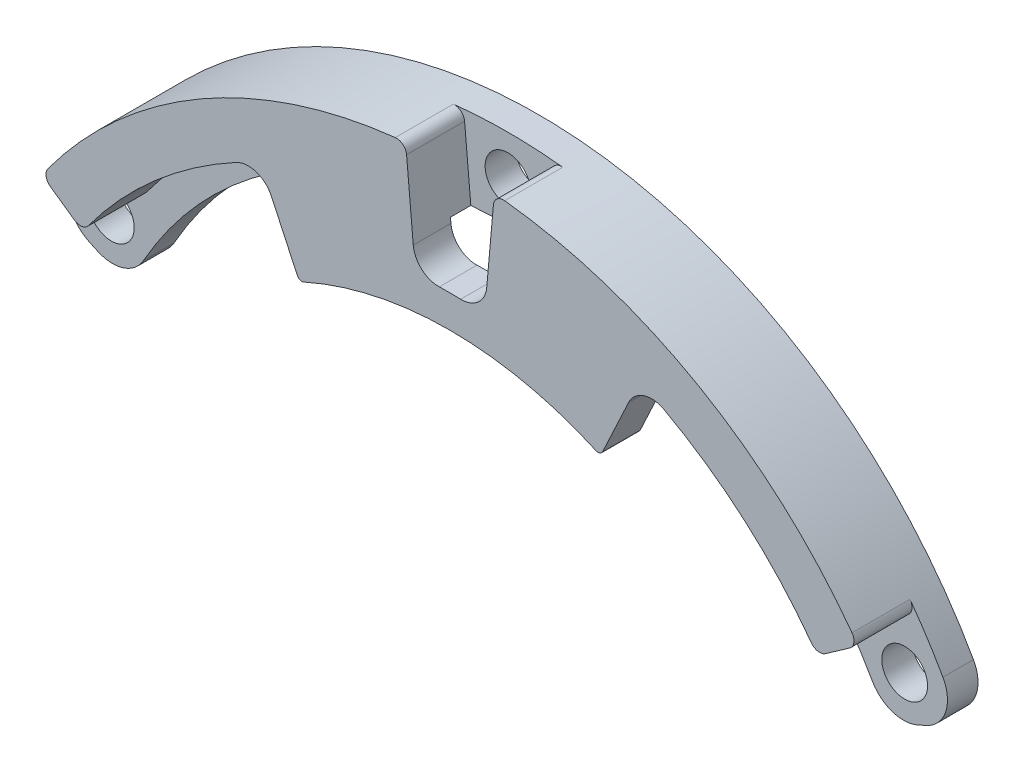
SolidWorks part; units mm, degrees
ref_plane "前视基准面" through (0, 0, 0) normal (0, 0, 1) x (1, 0, 0)
ref_plane "上视基准面" through (0, 0, 0) normal (0, 1, 0) x (1, 0, 0)
ref_plane "右视基准面" through (0, 0, 0) normal (1, 0, 0) x (0, 0, -1)
ref_plane "基准面1" through (0, 0, 8.7) normal (0, 0, 1) x (1, 0, 0)
sketch "草图1" plane through (0, 0, 8.7) normal (0, 0, 1) x (1, 0, 0)
  line L0 (14.7916, 31.7208) -> (18.6375, 39.9682)
  line L1 (36.0805, 25.3575) -> (40.0895, 28.175)
  line L2 (4.3556, 48.806) -> (3.3935, 38.0258)
  line L3 (-3.3935, 38.0258) -> (-4.3556, 48.806)
  line L4 (-40.0895, 28.175) -> (-36.0805, 25.3575)
  line L5 (-18.6375, 39.9682) -> (-14.7916, 31.7208)
  arc A0 (18.6375, 39.9682) -> (36.0805, 25.3575) centre (0, 0) cw
  arc A1 (40.0895, 28.175) -> (4.3556, 48.806) centre (0, 0) ccw
  arc A2 (3.3935, 38.0258) -> (-3.3935, 38.0258) centre (0, 0) ccw
  arc A3 (-4.3556, 48.806) -> (-40.0895, 28.175) centre (0, 0) ccw
  arc A4 (-36.0805, 25.3575) -> (-18.6375, 39.9682) centre (0, 0) cw
  arc A5 (-14.7916, 31.7208) -> (14.7916, 31.7208) centre (0, 0) cw
extrude "凸台-拉伸1" add sketch "草图1" against normal blind 3.7
sketch "草图2" plane through (0, 0, 5) normal (0, 0, -1) x (-1, 0, 0)
  line L0 (-36.0805, 25.3575) -> (-40.0895, 28.175)
  line L1 (-4.3556, 48.806) -> (-3.6533, 40.9373)
  line L2 (-17.3696, 37.2493) -> (-18.6375, 39.9682)
  arc A0 (-40.0895, 28.175) -> (-4.3556, 48.806) centre (0, 0) cw
  arc A1 (-3.6533, 40.9373) -> (-17.3696, 37.2493) centre (0, 0) ccw
  arc A2 (-18.6375, 39.9682) -> (-36.0805, 25.3575) centre (0, 0) ccw
extrude "凸台-拉伸2" add sketch "草图2" along normal blind 2
sketch "草图3" plane through (0, 0, 5) normal (0, 0, -1) x (-1, 0, 0)
  line L0 (3.6533, 40.9373) -> (4.3556, 48.806)
  line L1 (40.0895, 28.175) -> (36.0805, 25.3575)
  line L2 (18.6375, 39.9682) -> (17.3696, 37.2493)
  arc A0 (4.3556, 48.806) -> (40.0895, 28.175) centre (0, 0) cw
  arc A1 (36.0805, 25.3575) -> (18.6375, 39.9682) centre (0, 0) ccw
  arc A2 (17.3696, 37.2493) -> (3.6533, 40.9373) centre (0, 0) ccw
extrude "凸台-拉伸3" add sketch "草图3" along normal blind 2
ref_plane "基准面2" through (0, 0, 3) normal (0, 0, 1) x (1, 0, 0)
sketch "草图4" plane through (0, 0, 3) normal (0, 0, 1) x (1, 0, 0)
  line L0 (-44.445, 20.631) -> (-37.2794, 17.3048)
  line L1 (37.2794, 17.3048) -> (44.445, 20.631)
  arc A0 (-37.2794, 17.3048) -> (37.2794, 17.3048) centre (0, 0) cw
  arc A1 (44.445, 20.631) -> (-44.445, 20.631) centre (0, 0) ccw
extrude "凸台-拉伸4" add sketch "草图4" against normal blind 3
hole_wizard "Ø4.5 (4.5) 直径孔1" positions "草图6" profile "草图5" hole size "Ø4.5" standard "ANSI Metric"
sketch "草图6" plane through (0, 0, 3) normal (0, 0, 1) x (1, 0, 0)
  point P0 (-38.9711, 22.5)
  point P1 (38.9711, 22.5)
  point P2 (0, 45)
sketch "草图5" plane through (-38.9711, 22.5, 3) normal (1, 0, 0) x (0, -1, 0)
  line L0 (0, 0) -> (0, 3)
  line L1 (0, 3) -> (2.25, 3)
  line L2 (2.25, 3) -> (2.25, 0)
  line L5 (2.25, 0) -> (0, 0)
  line L11 (0, -6.35) -> (0, 107.95) construction
  dimension "通孔孔直径" = 4.5
  dimension "通孔孔深度" = 3
fillet "圆角1" radius 0.5 2 edges at (-14.7916, 31.7208, 6.85) (14.7916, 31.7208, 6.85)
fillet "圆角2" radius 1 6 edges at (-36.0805, 25.3575, 5.85) (-40.0895, 28.175, 5.85) (-4.3556, 48.806, 5.85) (36.0805, 25.3575, 5.85) (4.3556, 48.806, 5.85) (40.0895, 28.175, 5.85)
fillet "圆角3" radius 2.5 4 edges at (18.6375, 39.9682, 5.85) (3.3935, 38.0258, 6.85) (-3.3935, 38.0258, 6.85) (-18.6375, 39.9682, 5.85)
fillet "圆角4" radius 3.5 4 edges at (44.445, 20.631, 1.5) (-44.445, 20.631, 1.5) (37.2794, 17.3048, 1.5) (-37.2794, 17.3048, 1.5)
